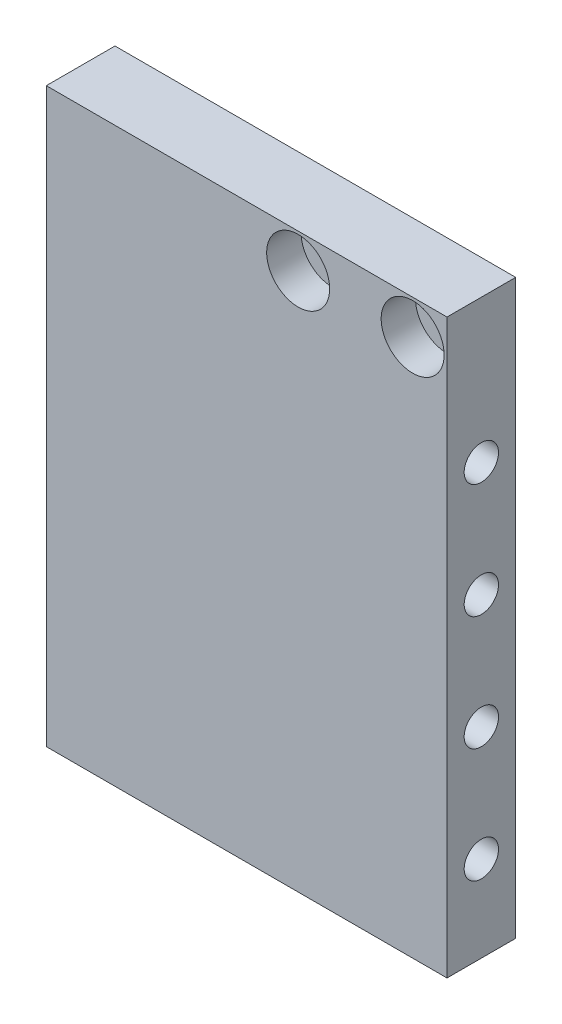
SolidWorks part; units mm, degrees
ref_plane "前视基准面" through (0, 0, 0) normal (0, 0, 1) x (1, 0, 0)
ref_plane "上视基准面" through (0, 0, 0) normal (0, 1, 0) x (1, 0, 0)
ref_plane "右视基准面" through (0, 0, 0) normal (1, 0, 0) x (0, 0, -1)
sketch "草图1" plane through (0, 0, 0) normal (0, 0, 1) x (1, 0, 0)
  line L1 (35, -50) -> (-35, -50)
  line L2 (35, -50) -> (35, 50)
  line L3 (35, 50) -> (-35, 50)
  line L4 (-35, -50) -> (-35, 50)
  line L5 (35, -50) -> (-35, 50) construction
  line L6 (35, 50) -> (-35, -50) construction
  point P0 (0, 0)
  dimension "D1" = 70
  dimension "D2" = 100
extrude "凸台-拉伸1" add sketch "草图1" along normal blind 12
sketch "草图2" plane through (-35, 0, 0) normal (-1, 0, 0) x (0, 0, 1)
  line L0 (12, -50) -> (0, -50) construction
  line L1 (12, 50) -> (12, -50) construction
  circle A0 centre (6, -35) radius 3
  circle A1 centre (6, -15) radius 3
  circle A2 centre (6, 5) radius 3
  circle A3 centre (6, 25) radius 3
  dimension "D1" = 6
  dimension "D2" = 6
  dimension "D3" = 6
  dimension "D4" = 6
  dimension "D5" = 20
  dimension "D6" = 20
  dimension "D7" = 20
  dimension "D8" = 15
extrude "切除-拉伸1" cut sketch "草图2" against normal blind 10
sketch "草图3" plane through (0, 0, 12) normal (0, 0, 1) x (1, 0, 0)
  line L0 (35, 50) -> (-35, 50) construction
  line L1 (35, -50) -> (35, 50) construction
  circle A0 centre (9, 44) radius 3
  circle A1 centre (29, 44) radius 3
  dimension "D1" = 6
  dimension "D5" = 6
  dimension "D6" = 6
  dimension "D2" = 6
  dimension "D3" = 20
  dimension "D4" = 6
extrude "切除-拉伸2" cut sketch "草图3" against normal blind 12
sketch "草图4" plane through (0, 0, 12) normal (0, 0, 1) x (1, 0, 0)
  circle A2 centre (9, 44) radius 5.5
  circle A3 centre (9, 44) radius 5.5
  circle A5 centre (29, 44) radius 5.5
  circle A6 centre (29, 44) radius 5.5
  dimension "D1" = 2.5
  dimension "D2" = 2.5
extrude "切除-拉伸3" cut sketch "草图4" against normal blind 6
sketch "草图5" plane through (35, 0, 0) normal (1, 0, 0) x (0, 0, -1)
  line L0 (-12, -50) -> (0, -50) construction
  line L2 (-12, -50) -> (-12, 50) construction
  line L3 (-6, -35) -> (-6, -15) construction
  circle A0 centre (-6, -35) radius 3
  circle A1 centre (-6, -15) radius 3
  circle A2 centre (-6, 5) radius 3
  circle A3 centre (-6, 25) radius 3
  dimension "D1" = 6
  dimension "D2" = 15
  dimension "D3" = 6
  dimension "D5" = 20
  dimension "D4" = 4
extrude "切除-拉伸4" cut sketch "草图5" against normal blind 10
sketch "草图6" plane through (0, -50, 0) normal (0, -1, 0) x (1, 0, 0)
  line L0 (-35, 12) -> (-35, 0) construction
  line L1 (-35, 12) -> (35, 12) construction
  circle A0 centre (-21, 6) radius 3
  circle A1 centre (-7, 6) radius 3
  circle A2 centre (7, 6) radius 3
  circle A3 centre (21, 6) radius 3
  dimension "D1" = 6
  dimension "D2" = 14
  dimension "D3" = 6
  dimension "D4" = 4
extrude "切除-拉伸5" cut sketch "草图6" against normal blind 10
